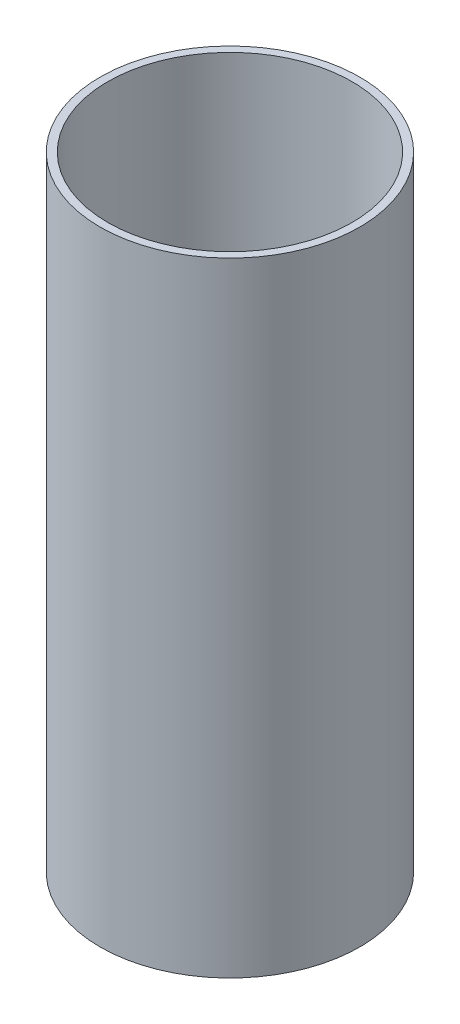
SolidWorks part; units mm, degrees
ref_plane "前视基准面" through (0, 0, 0) normal (0, 0, 1) x (1, 0, 0)
ref_plane "上视基准面" through (0, 0, 0) normal (0, 1, 0) x (1, 0, 0)
ref_plane "右视基准面" through (0, 0, 0) normal (1, 0, 0) x (0, 0, -1)
sketch "草图1" plane through (0, 0, 0) normal (0, 1, 0) x (1, 0, 0)
  circle A0 centre (0, 0) radius 25
  circle A1 centre (0, 0) radius 23.5
  dimension "D1" = 50
  dimension "D2" = 47
extrude "凸台-拉伸1" add sketch "草图1" along normal blind 120
